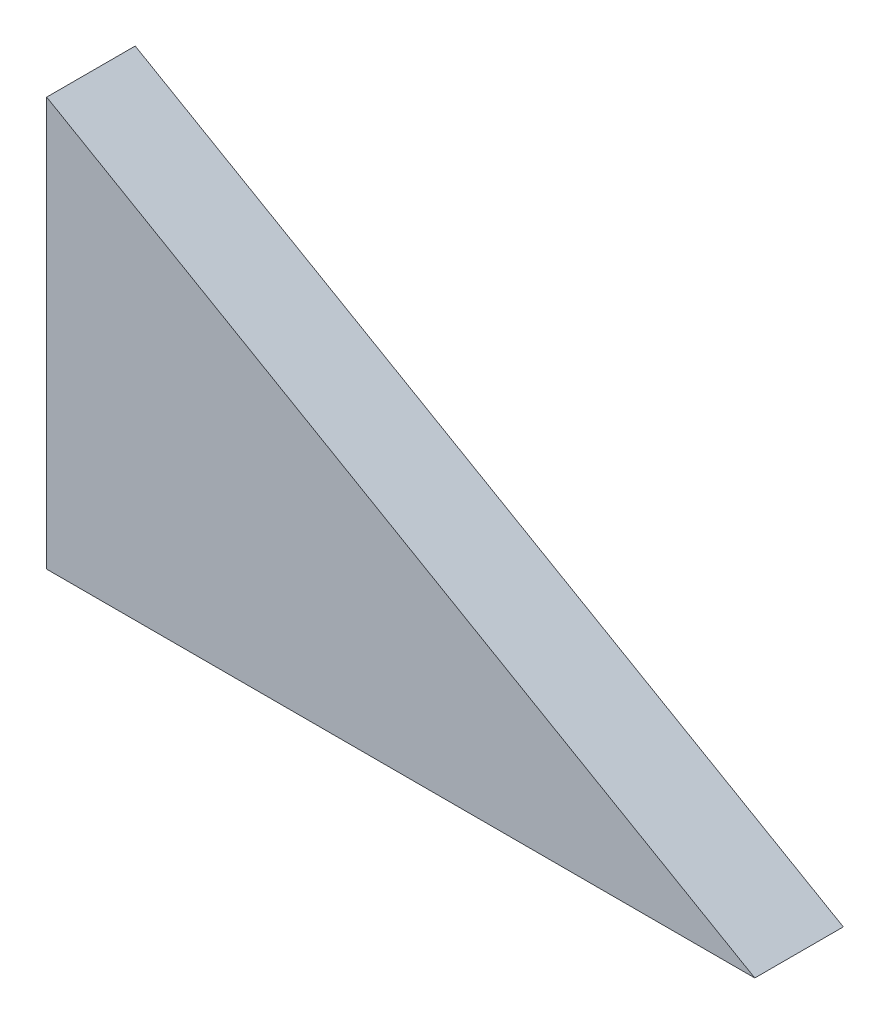
SolidWorks part; units mm, degrees
ref_plane "Plan de face" through (0, 0, 0) normal (0, 0, 1) x (1, 0, 0)
ref_plane "Plan de dessus" through (0, 0, 0) normal (0, 1, 0) x (1, 0, 0)
ref_plane "Plan de droite" through (0, 0, 0) normal (1, 0, 0) x (0, 0, -1)
sketch "Esquisse1" plane through (0, 0, 0) normal (0, 0, 1) x (1, 0, 0)
  line L0 (0, 0) -> (-40, 0)
  line L1 (-40, 0) -> (-40, 23.094)
  line L2 (-40, 23.094) -> (0, 0)
  point P4 (-20, 0)
  dimension "D1" = 40
  dimension "D2" = 10
extrude "Boss.-Extru.1" add sketch "Esquisse1" along normal blind 5
